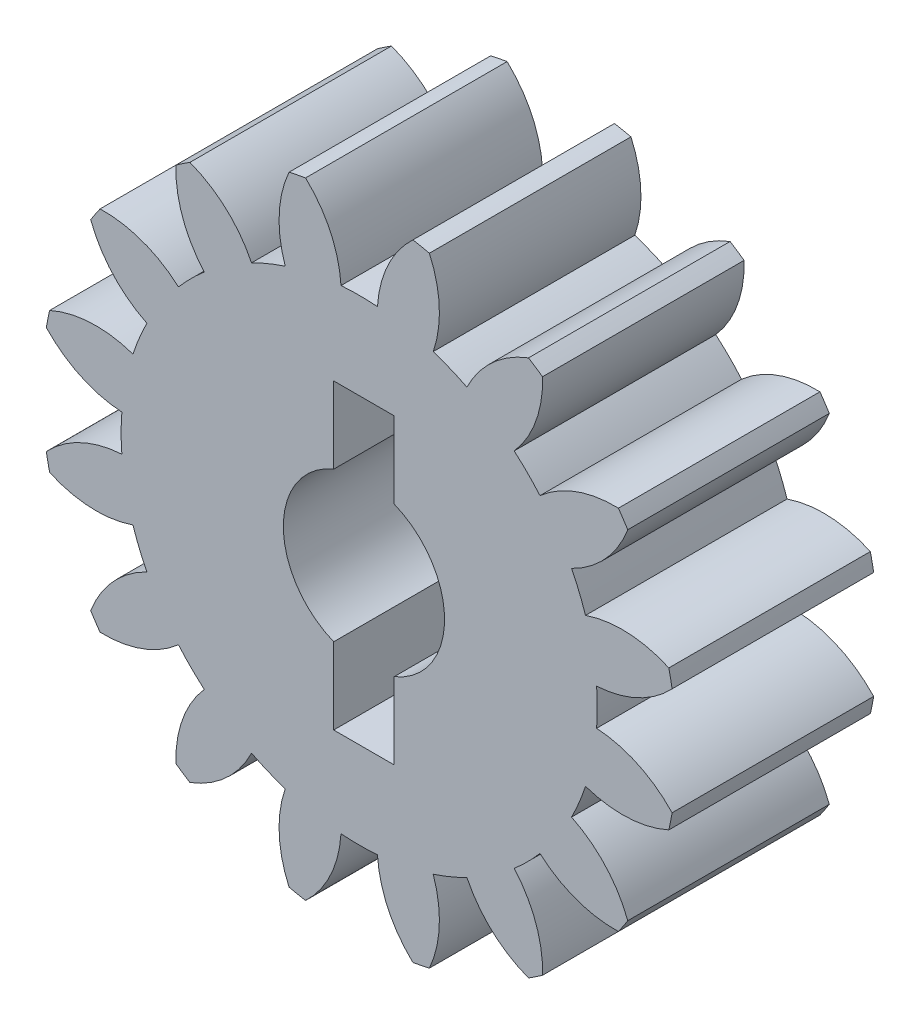
SolidWorks part; units mm, degrees
ref_plane "Front Plane" through (0, 0, 0) normal (0, 0, 1) x (1, 0, 0)
ref_plane "Top Plane" through (0, 0, 0) normal (0, 1, 0) x (1, 0, 0)
ref_plane "Right Plane" through (0, 0, 0) normal (1, 0, 0) x (0, 0, -1)
sketch "Sketch1" plane through (0, 0, 0) normal (0, 0, 1) x (1, 0, 0)
  line L0 (-3, 15) -> (3, 15)
  line L1 (-3, 15) -> (-3, 7.4162)
  line L2 (-3, -15) -> (3, -15)
  line L3 (3, 15) -> (3, 7.4162)
  line L6 (3, -7.4162) -> (3, -15)
  line L9 (-3, -7.4162) -> (-3, -15)
  arc A0 (-31.5151, 5.3236) -> (-24.0228, 1.8098) centre (-23.3497, 12.9895) ccw
  arc A1 (-24.0228, 1.8098) -> (-24.0228, -1.8098) centre (-0.4682, 0) ccw
  arc A2 (-24.0228, -1.8098) -> (-31.5151, -5.3236) centre (-23.3497, -12.9895) ccw
  arc A3 (-31.5151, -5.3236) -> (-31.189, -6.9627) centre (-0.4682, 0) ccw
  arc A4 (-31.189, -6.9627) -> (-22.9224, -7.3419) centre (-26.5788, 3.2444) ccw
  arc A5 (-22.9224, -7.3419) -> (-21.5372, -10.686) centre (-0.4682, 0) ccw
  arc A6 (-21.5372, -10.686) -> (-27.1145, -16.7995) centre (-16.637, -20.7571) ccw
  arc A7 (-27.1145, -16.7995) -> (-26.186, -18.1891) centre (-0.4682, 0) ccw
  arc A8 (-26.186, -18.1891) -> (-18.4035, -15.3759) centre (-25.8328, -6.9947) ccw
  arc A9 (-18.4035, -15.3759) -> (-15.8441, -17.9353) centre (-0.4682, 0) ccw
  arc A10 (-15.8441, -17.9353) -> (-18.6573, -25.7178) centre (-7.4629, -25.3646) ccw
  arc A11 (-18.6573, -25.7178) -> (-17.2677, -26.6463) centre (-0.4682, 0) ccw
  arc A12 (-17.2677, -26.6463) -> (-11.1542, -21.069) centre (-21.2253, -16.1688) ccw
  arc A13 (-11.1542, -21.069) -> (-7.8101, -22.4542) centre (-0.4682, 0) ccw
  arc A14 (-7.8101, -22.4542) -> (-7.4309, -30.7208) centre (2.7762, -26.1106) ccw
  arc A15 (-7.4309, -30.7208) -> (-5.7918, -31.0469) centre (-0.4682, 0) ccw
  arc A16 (-5.7918, -31.0469) -> (-2.278, -23.5546) centre (-13.4577, -22.8815) ccw
  arc A17 (-2.278, -23.5546) -> (1.3416, -23.5546) centre (-0.4682, 0) ccw
  arc A18 (1.3416, -23.5546) -> (4.8554, -31.0469) centre (12.5213, -22.8815) ccw
  arc A19 (4.8554, -31.0469) -> (6.4945, -30.7208) centre (-0.4682, 0) ccw
  arc A20 (6.4945, -30.7208) -> (6.8737, -22.4542) centre (-3.7126, -26.1106) ccw
  arc A21 (6.8737, -22.4542) -> (10.2178, -21.069) centre (-0.4682, 0) ccw
  arc A22 (10.2178, -21.069) -> (16.3313, -26.6463) centre (20.2889, -16.1688) ccw
  arc A23 (16.3313, -26.6463) -> (17.7209, -25.7178) centre (-0.4682, 0) ccw
  arc A24 (17.7209, -25.7178) -> (14.9077, -17.9353) centre (6.5265, -25.3646) ccw
  arc A25 (14.9077, -17.9353) -> (17.4671, -15.3759) centre (-0.4682, 0) ccw
  arc A26 (17.4671, -15.3759) -> (25.2496, -18.1891) centre (24.8964, -6.9947) ccw
  arc A27 (25.2496, -18.1891) -> (26.1781, -16.7995) centre (-0.4682, 0) ccw
  arc A28 (26.1781, -16.7995) -> (20.6008, -10.686) centre (15.7006, -20.7571) ccw
  arc A29 (20.6008, -10.686) -> (21.986, -7.3419) centre (-0.4682, 0) ccw
  arc A30 (21.986, -7.3419) -> (30.2526, -6.9627) centre (25.6424, 3.2444) ccw
  arc A31 (30.2526, -6.9627) -> (30.5787, -5.3236) centre (-0.4682, 0) ccw
  arc A32 (30.5787, -5.3236) -> (23.0864, -1.8098) centre (22.4133, -12.9895) ccw
  arc A33 (23.0864, -1.8098) -> (23.0864, 1.8098) centre (-0.4682, 0) ccw
  arc A34 (23.0864, 1.8098) -> (30.5787, 5.3236) centre (22.4133, 12.9895) ccw
  arc A35 (30.5787, 5.3236) -> (30.2526, 6.9627) centre (-0.4682, 0) ccw
  arc A36 (30.2526, 6.9627) -> (21.986, 7.3419) centre (25.6424, -3.2444) ccw
  arc A37 (21.986, 7.3419) -> (20.6008, 10.686) centre (-0.4682, 0) ccw
  arc A38 (20.6008, 10.686) -> (26.1781, 16.7995) centre (15.7006, 20.7571) ccw
  arc A39 (26.1781, 16.7995) -> (25.2496, 18.1891) centre (-0.4682, 0) ccw
  arc A40 (25.2496, 18.1891) -> (17.4671, 15.3759) centre (24.8964, 6.9947) ccw
  arc A41 (17.4671, 15.3759) -> (14.9077, 17.9353) centre (-0.4682, 0) ccw
  arc A42 (14.9077, 17.9353) -> (17.7209, 25.7178) centre (6.5265, 25.3646) ccw
  arc A43 (17.7209, 25.7178) -> (16.3313, 26.6463) centre (-0.4682, 0) ccw
  arc A44 (16.3313, 26.6463) -> (10.2178, 21.069) centre (20.2889, 16.1688) ccw
  arc A45 (10.2178, 21.069) -> (6.8737, 22.4542) centre (-0.4682, 0) ccw
  arc A46 (6.8737, 22.4542) -> (6.4945, 30.7208) centre (-3.7126, 26.1106) ccw
  arc A47 (6.4945, 30.7208) -> (4.8554, 31.0469) centre (-0.4682, 0) ccw
  arc A48 (4.8554, 31.0469) -> (1.3416, 23.5546) centre (12.5213, 22.8815) ccw
  arc A49 (1.3416, 23.5546) -> (-2.278, 23.5546) centre (-0.4682, 0) ccw
  arc A50 (-2.278, 23.5546) -> (-5.7918, 31.0469) centre (-13.4577, 22.8815) ccw
  arc A51 (-5.7918, 31.0469) -> (-7.4309, 30.7208) centre (-0.4682, 0) ccw
  arc A52 (-7.4309, 30.7208) -> (-7.8101, 22.4542) centre (2.7762, 26.1106) ccw
  arc A53 (-7.8101, 22.4542) -> (-11.1542, 21.069) centre (-0.4682, 0) ccw
  arc A54 (-11.1542, 21.069) -> (-17.2677, 26.6463) centre (-21.2253, 16.1688) ccw
  arc A55 (-17.2677, 26.6463) -> (-18.6573, 25.7178) centre (-0.4682, 0) ccw
  arc A56 (-18.6573, 25.7178) -> (-15.8441, 17.9353) centre (-7.4629, 25.3646) ccw
  arc A57 (-15.8441, 17.9353) -> (-18.4035, 15.3759) centre (-0.4682, 0) ccw
  arc A58 (-18.4035, 15.3759) -> (-26.186, 18.1891) centre (-25.8328, 6.9947) ccw
  arc A59 (-26.186, 18.1891) -> (-27.1145, 16.7995) centre (-0.4682, 0) ccw
  arc A60 (-27.1145, 16.7995) -> (-21.5372, 10.686) centre (-16.637, 20.7571) ccw
  arc A61 (-21.5372, 10.686) -> (-22.9224, 7.3419) centre (-0.4682, 0) ccw
  arc A62 (-22.9224, 7.3419) -> (-31.189, 6.9627) centre (-26.5788, -3.2444) ccw
  arc A63 (-31.189, 6.9627) -> (-31.5151, 5.3236) centre (-0.4682, 0) ccw
  arc A64 (-3, 7.4162) -> (-3, -7.4162) centre (0, 0) ccw
  arc A65 (3, -7.4162) -> (3, 7.4162) centre (0, 0) ccw
  point P128 (0, 0)
  point P129 (0, 0)
  point P135 (3, -11.2081)
  dimension "D3" = 16
  dimension "D1" = 30
  dimension "D2" = 6
extrude "Boss-Extrude1" add sketch "Sketch1" along normal blind 20
